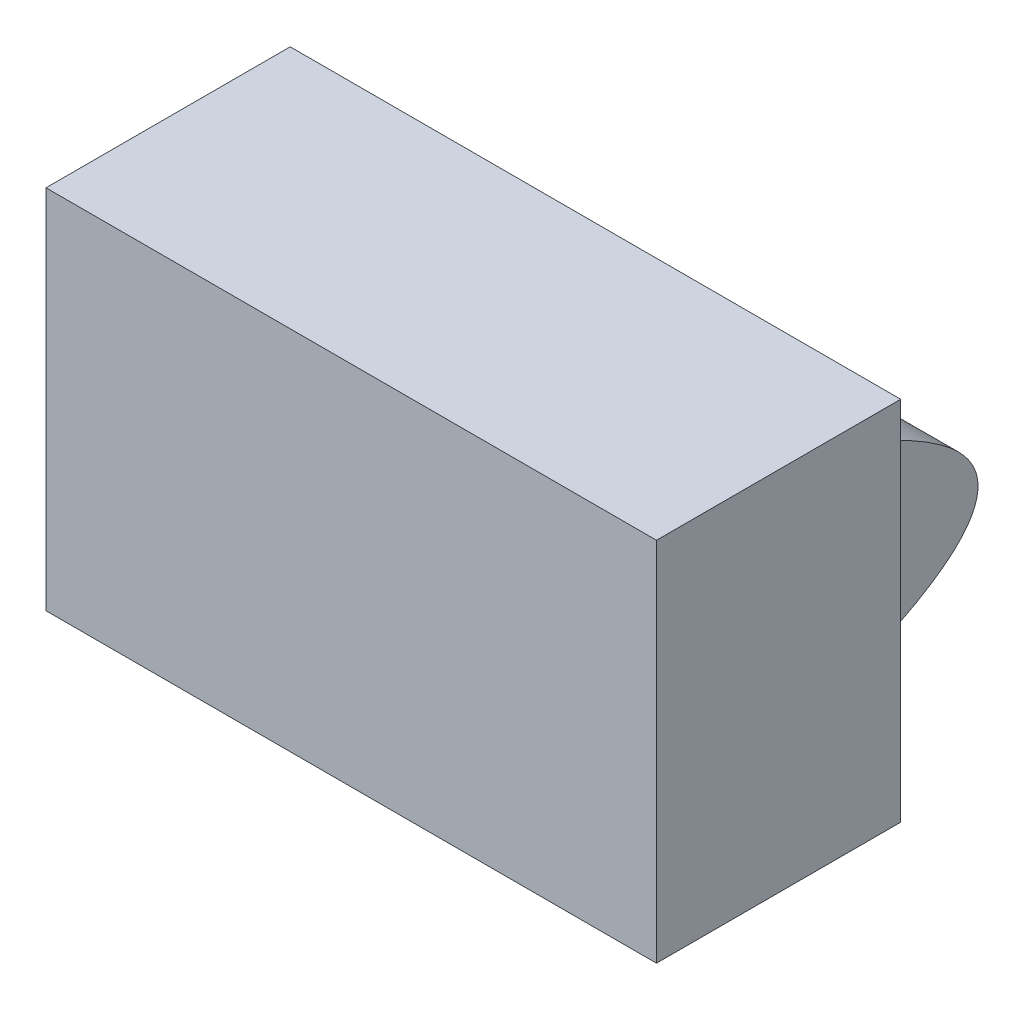
SolidWorks part; units mm, degrees
ref_plane "前视基准面" through (0, 0, 0) normal (0, 0, 1) x (1, 0, 0)
ref_plane "上视基准面" through (0, 0, 0) normal (0, 1, 0) x (1, 0, 0)
ref_plane "右视基准面" through (0, 0, 0) normal (1, 0, 0) x (0, 0, -1)
sketch "草图1" plane through (0, 0, 0) normal (0, 1, 0) x (1, 0, 0)
  line L1 (0, 0) -> (-7.5, 0)
  line L2 (0, 0) -> (0, 3)
  line L3 (0, 3) -> (-7.5, 3)
  line L4 (-7.5, 0) -> (-7.5, 3)
  dimension "D1" = 7.5
  dimension "D2" = 3
extrude "凸台-拉伸1" add sketch "草图1" along normal blind 4.5
sketch "草图2" plane through (0, 0, -3) normal (0, 0, -1) x (-1, 0, 0)
  line L0 (3.75, -993.8986) -> (3.75, 49006.1014) construction
  line L1 (0.65, 3.7) -> (1.85, 3.7)
  line L2 (0.65, 3.7) -> (0.65, 1.2)
  line L3 (0.65, 1.2) -> (1.85, 1.2)
  line L4 (1.85, 3.7) -> (1.85, 1.2)
  line L5 (3.15, 3.7) -> (4.35, 3.7)
  line L6 (3.15, 3.7) -> (3.15, 1.2)
  line L7 (3.15, 1.2) -> (4.35, 1.2)
  line L8 (4.35, 3.7) -> (4.35, 1.2)
  line L9 (5.65, 3.7) -> (6.85, 3.7)
  line L10 (5.65, 3.7) -> (5.65, 1.2)
  line L11 (5.65, 1.2) -> (6.85, 1.2)
  line L12 (6.85, 3.7) -> (6.85, 1.2)
  line L13 (0, 4.5) -> (0, 0) construction
  line L14 (7.5, 4.5) -> (7.5, 0) construction
  line L15 (0, 0) -> (7.5, 0) construction
  point P18 (1.25, 1.2)
  point P19 (3.75, 1.2)
  point P20 (6.25, 1.2)
  dimension "D1" = 2.5
  dimension "D2" = 1.2
  dimension "D3" = 2.5
  dimension "D4" = 2.5
  dimension "D5" = 1.2
extrude "凸台-拉伸2" add sketch "草图2" along normal blind 1.6
sketch "草图3" plane through (-0.65, 0, 0) normal (1, 0, 0) x (0, 0, -1)
  line L0 (4.6, 3.7) -> (4.6, 1.2) construction
  line L1 (3, 1.2) -> (4.6, 1.2)
  line L2 (4.6, 1.2) -> (4.6, 3.7)
  line L3 (4.6, 3.7) -> (3, 3.7)
  spline S0 degree 2 poles (3, 1.2) (6.2, 2.45) (3, 3.7) knots 0 0 0 1 1 1
  line M2 (3, 1.2) -> (4.6, 1.2)
  line M3 (4.6, 1.2) -> (4.6, 3.7)
  line M4 (4.6, 3.7) -> (3, 3.7)
extrude "切除-拉伸1" cut sketch "草图3" against normal through all contours S0 L2 M4 | S0 M2 M3
